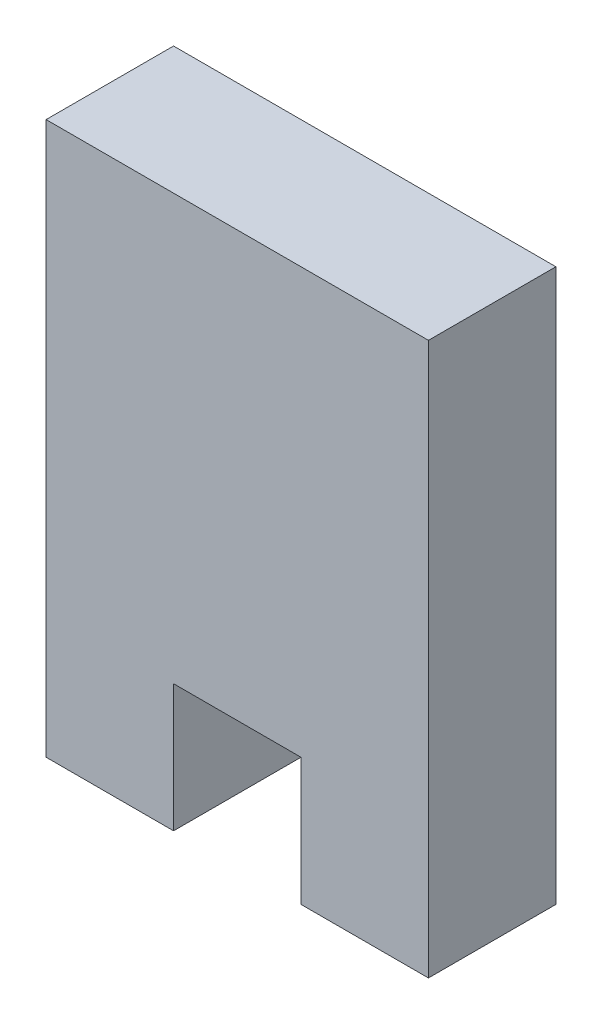
SolidWorks part; units mm, degrees
ref_plane "Front Plane" through (0, 0, 0) normal (0, 0, 1) x (1, 0, 0)
ref_plane "Top Plane" through (0, 0, 0) normal (0, 1, 0) x (1, 0, 0)
ref_plane "Right Plane" through (0, 0, 0) normal (1, 0, 0) x (0, 0, -1)
sketch "Sketch1" plane through (0, 0, 0) normal (0, 0, 1) x (1, 0, 0)
  line L0 (-4.5816, -20.3418) -> (-1.5816, -20.3418)
  line L1 (-10.5816, -7.3418) -> (-1.5816, -7.3418)
  line L2 (-10.5816, -7.3418) -> (-10.5816, -20.3418)
  line L3 (-10.5816, -20.3418) -> (-7.5816, -20.3418)
  line L4 (-1.5816, -7.3418) -> (-1.5816, -20.3418)
  line L5 (-7.5816, -17.3418) -> (-4.5816, -17.3418)
  line L6 (-7.5816, -17.3418) -> (-7.5816, -20.3418)
  line L8 (-4.5816, -17.3418) -> (-4.5816, -20.3418)
  dimension "D1" = 9
  dimension "D2" = 13
  dimension "D3" = 3
  dimension "D4" = 3
  dimension "D6" = 3
extrude "Boss-Extrude1" add sketch "Sketch1" along normal blind 3
